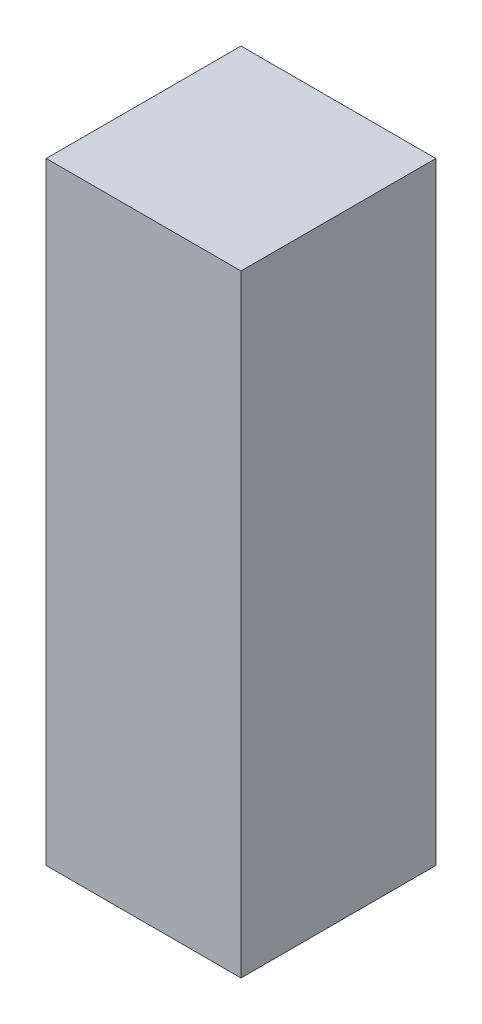
SolidWorks part; units mm, degrees
ref_plane "前视基准面" through (0, 0, 0) normal (0, 0, 1) x (1, 0, 0)
ref_plane "上视基准面" through (0, 0, 0) normal (0, 1, 0) x (1, 0, 0)
ref_plane "右视基准面" through (0, 0, 0) normal (1, 0, 0) x (0, 0, -1)
other "Configuration Table"
sketch "草图1" plane through (0, 0, 0) normal (0, 1, 0) x (1, 0, 0)
  line L1 (-0.35, 0.35) -> (0.35, 0.35)
  line L2 (-0.35, 0.35) -> (-0.35, -0.35)
  line L3 (-0.35, -0.35) -> (0.35, -0.35)
  line L4 (0.35, 0.35) -> (0.35, -0.35)
  line L5 (-0.35, 0.35) -> (0.35, -0.35) construction
  line L6 (-0.35, -0.35) -> (0.35, 0.35) construction
  point P0 (0, 0)
  dimension "D1" = 0.7
  dimension "D2" = 0.7
extrude "凸台-拉伸1" add sketch "草图1" along normal blind 2.2
